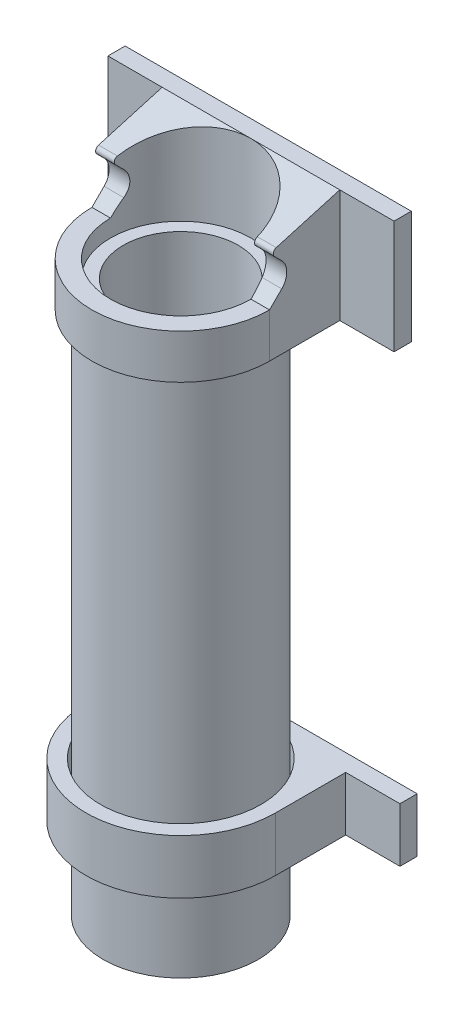
SolidWorks part; units mm, degrees
other "pipe" parameters "D1"=877.6559, "D2"=75.5022, "D3"=726.6514, "D4"=726.6514, "D5"=877.6559, "D6"=4.445, "D7"=9.9955, "\"bearing_bore_min\""=42.164, "D8"=59.5421, "D9"=6.35, "D10"=1.4503
material "6061 Alloy"
ref_plane "Front Plane" through (0, 0, 0) normal (0, 0, 1) x (1, 0, 0)
ref_plane "Top Plane" through (0, 0, 0) normal (0, 1, 0) x (1, 0, 0)
ref_plane "Right Plane" through (0, 0, 0) normal (1, 0, 0) x (0, 0, -1)
sketch "Sketch11" plane through (0, 0, 0) normal (0, 0, 1) x (1, 0, 0)
  line L0 (0, 0) -> (0, 109.6398) construction
  line L1 (0, 0) -> (-89.1372, 0) construction
sketch "Sketch12" plane through (0, 0, 0) normal (0, 0, 1) x (1, 0, 0)
  line L0 (-28.575, 0) -> (-28.575, 203.2)
  line L1 (200000, 0) -> (-200089.1372, 0) construction
  line L4 (-21.2287, 0) -> (-28.575, 0)
  line L5 (-21.2287, 0) -> (-21.2287, 38.5)
  line L6 (-21.2287, 38.5) -> (-19.177, 38.5)
  line L7 (-19.177, 38.5) -> (-19.177, 164.7)
  line L8 (-19.177, 164.7) -> (-21.2287, 164.7)
  line L9 (-21.2287, 164.7) -> (-21.2287, 203.2)
  line L10 (-21.2287, 203.2) -> (-28.575, 203.2)
  line L13 (-21.2287, 203.2) -> (0, 203.2) construction
  line L14 (0, 203.2) -> (0, 0) construction
  line L15 (0, 0) -> (-21.2287, 0) construction
  point P12 (-25.4, 0)
  dimension "D4" = 38.5
  dimension "D5" = 203.2
  dimension "D6" = 7.3463
  dimension "D1" = 57.15
  dimension "D2" = 42.4573
  dimension "D8" = 50.8
  dimension "D9" = 3.175
  dimension "D3" = 38.354
  dimension "D7" = 2.0517
revolve "Revolve1" add sketch "Sketch12" angle 360 about L0
ref_plane "mideplane" through (0, 101.6, 0) normal (0, -1, 0) x (-1, 0, 0)
ref_plane "top pipe plane" through (0, 30, 0) normal (0, -1, 0) x (-1, 0, 0)
ref_plane "bottom pipe plane" through (0, 203.2, 0) normal (0, 1, 0) x (1, 0, 0)
ref_plane "pipe support midplane" through (0, 116.6, 0) normal (0, -1, 0) x (-1, 0, 0)
ref_plane "support plane" through (0, 193.2, 0) normal (0, 1, 0) x (1, 0, 0)
sketch "Sketch15" plane through (0, 193.2, 0) normal (0, 1, 0) x (1, 0, 0)
  line L0 (32.75, 0) -> (32.75, 32.25)
  line L1 (32.75, 32.25) -> (-32.75, 32.25)
  line L2 (-32.75, 32.25) -> (-32.75, 0)
  line L3 (32.75, 25.9) -> (-32.75, 25.9)
  circle A0 centre (0, 0) radius 25.9
  circle A2 centre (0, 0) radius 25.4 construction
  circle A3 centre (0, 0) radius 28.575 construction
  circle A4 centre (0, 0) radius 28.575
  circle A5 centre (0, 0) radius 29.575
  circle A6 centre (0, 0) radius 32.75
  dimension "D1" = 51.8
  dimension "D3" = 50.8
  dimension "D2" = 2.675
  dimension "D4" = 1
  dimension "D5" = 3.175
  dimension "D6" = 6.35
extrude "Boss-Extrude1" add sketch "Sketch15" along normal up to surface (10 mm away) separate body contours A6 L1 L2 L3 | A6 L3 L2 | A6 L3 L0 L1 | A6 L0 L3 | A6 L3 A5 | L3 A6 L1 A5 up to face at (0, 203.2, -28.575)
sketch "Sketch16" plane through (0, 203.2, 0) normal (0, 1, 0) x (1, 0, 0)
  line L0 (32.75, 0) -> (32.75, 32.25) construction
  line L1 (-32.75, 32.25) -> (-32.75, 0) construction
  line L2 (32.75, 32.25) -> (-32.75, 32.25) construction
  line L3 (32.75, 0) -> (32.75, 32.25)
  line L4 (-32.75, 32.25) -> (-32.75, 0)
  line L5 (32.75, 32.25) -> (-32.75, 32.25)
  circle A0 centre (0, 0) radius 32.75 construction
  circle A1 centre (0, 0) radius 25.9 construction
  circle A2 centre (0, 0) radius 32.75
  circle A3 centre (0, 0) radius 25.9
  circle M1 centre (0, 0) radius 29.575
  arc M2 (-32.75, 0) -> (32.75, 0) centre (0, 0) ccw
  line M3 (32.75, 0) -> (32.75, 32.25)
  line M4 (32.75, 32.25) -> (-32.75, 32.25)
  line M5 (-32.75, 32.25) -> (-32.75, 0)
extrude "Boss-Extrude2" add sketch "Sketch16" along normal blind 6.35 contours A2 M3 M4 | A2 M4 M5 | A2 L5 M2 M1 | A3 M1
sketch "Sketch17" plane through (0, 209.55, 0) normal (0, 1, 0) x (1, 0, 0)
  line L0 (32.75, 25.9) -> (-32.75, 25.9)
  line L1 (32.75, 0) -> (32.75, 32.25) construction
  line L2 (-32.75, 32.25) -> (-32.75, 0) construction
  line L3 (32.75, 0) -> (25.9, 0)
  line L4 (-25.9, 0) -> (-32.75, 0)
  circle A0 centre (0, 0) radius 25.9 construction
  circle A1 centre (0, 0) radius 25.9
  point P13 (0, 0)
  point P14 (0, 0)
  line M2 (32.75, 32.25) -> (-32.75, 32.25)
  line M3 (-32.75, 32.25) -> (-32.75, 0)
  line M5 (32.75, 0) -> (32.75, 32.25)
  circle M6 centre (0, 0) radius 25.9
extrude "Boss-Extrude3" add sketch "Sketch17" along normal blind 25.4 contours L0 M5 M2 M3 | L3 L0 M5 M6 | L4 L0 M6 M3
sketch "Sketch18" plane through (-32.75, 0, 0) normal (-1, 0, 0) x (0, 0, 1)
  line L4 (-25.9, 234.95) -> (0, 227.5105)
  line L6 (-32.25, 234.95) -> (0, 234.95) construction
  line L7 (-4.4901, 223.0204) -> (0, 227.5105)
  line L8 (0, 218.5303) -> (-4.4901, 223.0204) construction
  line L9 (-4.4901, 214.0401) -> (0, 209.55)
  line L10 (-4.4901, 214.0401) -> (0, 218.5303) construction
  line L12 (0, 234.95) -> (0, 209.55) construction
  line L13 (0, 234.95) -> (0, 209.55)
  circle A0 centre (0, 218.5303) radius 6.35
  circle A1 centre (-2.8604, 226.7715) radius 1.5
  point P1 (0, 0)
  point P3 (0, 0)
  point P10 (0, 227.5035)
  point P11 (-23.8894, 231.0769)
  point P14 (0, 0)
  point P17 (0, 0)
  point P19 (0, 0)
  point P20 (0, 0)
  point P21 (0.3486, 209.55)
  point P22 (0, 227.5105)
  point P23 (-19.6868, 234.95)
  point P24 (-26.9054, 234.95)
  point P25 (-25.0137, 234.95)
  line M10 (0, 234.95) -> (-32.25, 234.95)
  line M19 (0, 209.55) -> (0, 234.95)
  dimension "D1" = 12.7
  dimension "D4" = 3
  dimension "D2" = 45
  dimension "D3" = 45
  dimension "D5" = 6.35
extrude "Cut-Extrude1" cut sketch "Sketch18" against normal through all both and the other way through all contours A0 L7 M19 | A1 L7 L4 | L13 A0 | A0 L9 M19 | L13 A0 | L4 M10 M19
sketch "Sketch19" plane through (32.75, 0, 0) normal (1, 0, 0) x (0, 0, -1)
  line L0 (25.9, 234.95) -> (25.9, 193.2)
  line L1 (0, 193.2) -> (32.25, 193.2) construction
  point P3 (25.9, 193.2)
  line M1 (32.25, 234.95) -> (25.9, 234.95)
  line M8 (0, 193.2) -> (32.25, 193.2)
  line M9 (32.25, 193.2) -> (32.25, 234.95)
extrude "Boss-Extrude5" add sketch "Sketch19" along normal blind 20 contours L0 M1 M8 M9
mirror "Mirror1" about plane through (0, 0, 0) normal (1, 0, 0) of "Boss-Extrude5"
sketch "Sketch20" plane through (0, 30, 0) normal (0, -1, 0) x (-1, 0, 0)
  line L0 (34.925, 0) -> (34.925, 32.25)
  line L1 (34.925, 32.25) -> (-34.925, 32.25)
  line L2 (-34.925, 32.25) -> (-34.925, 0)
  line L3 (-52.75, 32.25) -> (52.75, 32.25) construction
  line L4 (-52.75, 32.25) -> (52.75, 32.25) construction
  line L5 (-34.925, 32.25) -> (-54.925, 32.25)
  line L6 (-54.925, 32.25) -> (-54.925, 25.9)
  line L7 (-54.925, 25.9) -> (-34.925, 25.9)
  line L8 (34.925, 32.25) -> (54.925, 32.25)
  line L9 (54.925, 32.25) -> (54.925, 25.9)
  line L10 (54.925, 25.9) -> (34.925, 25.9)
  circle A0 centre (0, 0) radius 28.575 construction
  circle A1 centre (0, 0) radius 28.575
  circle A2 centre (0, 0) radius 29.575
  circle A3 centre (0, 0) radius 34.925
  dimension "D3" = 6.35
  dimension "D4" = 6.35
  dimension "D5" = 20
  dimension "D6" = 20
  dimension "D1" = 1
  dimension "D2" = 6.35
extrude "Boss-Extrude6" add sketch "Sketch20" against normal blind 20 separate body contours A3 L0 L1 | L10 L9 L8 L0 | L1 A3 A2 | A3 L1 L2 | L6 L7 L2 L5
equation "\"bearing_bore\"= 1 + 21 / 32in"
equation "\"bearing_bore_max\"= 1.6568in"
equation "\"bearing_bore_min\"= 1.6558in"
equation "\"shaft_dia\"= 1.5in"
equation "\"shaft_dia_min\"= 1.51in"
equation "\"D2@Sketch12\"=\"bearing_bore_min\"+0.4mm"
equation "\"bearing_flange_diameter\"= 2in"
equation "\"bearing_flange_thickness\"= 0.078in"
equation "\"bearing_length\"= 1.5in"
equation "\"D8@Sketch12\"=\"bearing_flange_diameter\""
equation "\"D4@Sketch12\"=\"bearing_length\"+0.4"
equation "\"nub_dia\"= 0.5in"
equation "\"D1@Sketch12\"=2.25in"
equation "\"D1@Sketch15\"=\"bearing_flange_diameter\"+1mm"
equation "\"D3@Sketch15\"=\"bearing_flange_diameter\""
